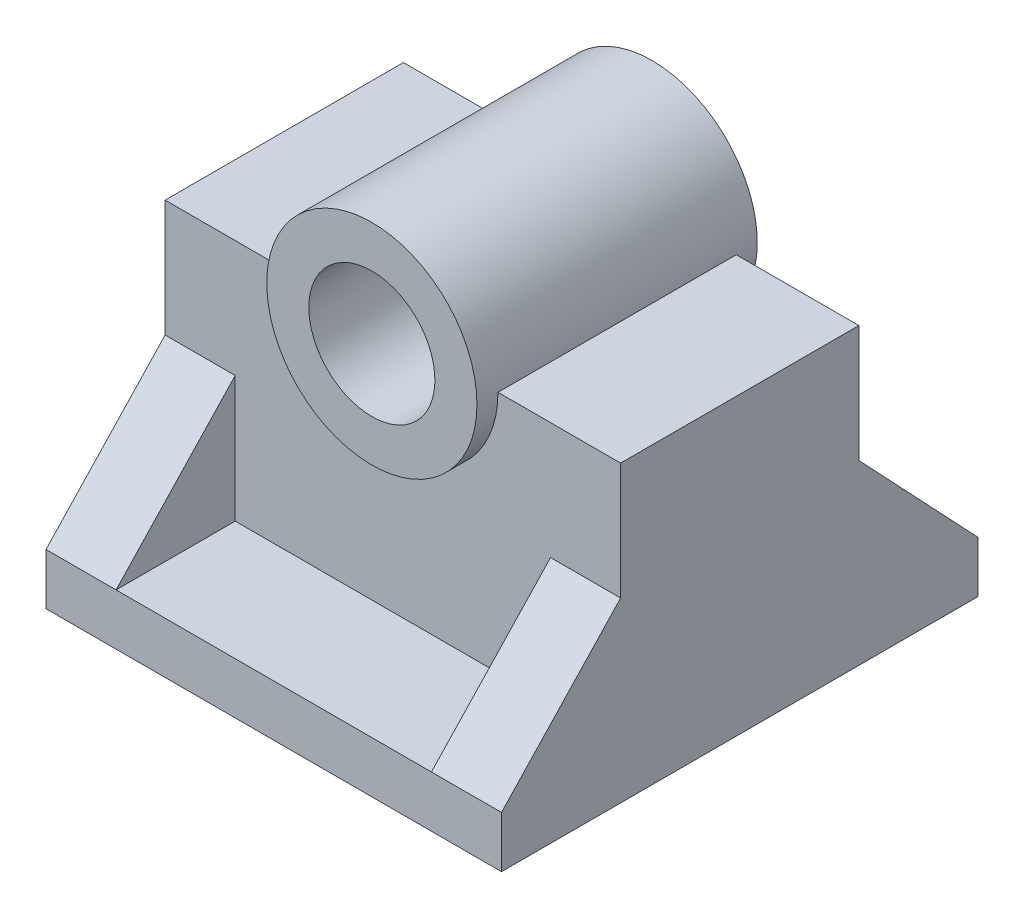
SolidWorks part; units mm, degrees
ref_plane "Front Plane" through (0, 0, 0) normal (0, 0, 1) x (1, 0, 0)
ref_plane "Top Plane" through (0, 0, 0) normal (0, 1, 0) x (1, 0, 0)
ref_plane "Right Plane" through (0, 0, 0) normal (1, 0, 0) x (0, 0, -1)
sketch "Sketch1" plane through (0, 0, 0) normal (1, 0, 0) x (0, 0, -1)
  line L0 (-50.2559, -9.9024) -> (-50.2559, -2.5758)
  line L1 (-50.2559, -2.5758) -> (-33.2559, -2.5758)
  line L2 (-33.2559, -2.5758) -> (-33.2559, 32.0976)
  line L3 (-33.2559, 32.0976) -> (0.7441, 32.0976)
  line L4 (0.7441, 32.0976) -> (0.7441, -2.5758)
  line L5 (0.7441, -2.5758) -> (17.7441, -2.5758)
  line L6 (17.7441, -2.5758) -> (17.7441, -9.9024)
  line L7 (17.7441, -9.9024) -> (-50.2559, -9.9024)
  dimension "D1" = 68
  dimension "D2" = 42
  dimension "D3" = 34
  dimension "D4" = 17
extrude "Boss-Extrude1" add sketch "Sketch1" against normal blind 65
sketch "Sketch2" plane through (0, 0, 0) normal (1, 0, 0) x (0, 0, -1)
  line L0 (-33.2559, 15.4242) -> (-50.2559, -2.5758)
  line L1 (-33.2559, 32.0976) -> (-33.2559, -2.5758) construction
  line L2 (-50.2559, -2.5758) -> (-33.2559, -2.5758)
  line L3 (-33.2559, -2.5758) -> (-33.2559, 15.4242)
  dimension "D1" = 18
extrude "Boss-Extrude2" add sketch "Sketch2" against normal blind 10
sketch "Sketch3" plane through (-65, 0, 0) normal (-1, 0, 0) x (0, 0, 1)
  line L0 (33.2559, 15.4242) -> (50.2559, -2.5758)
  line L1 (50.2559, -2.5758) -> (33.2559, -2.5758)
  line L2 (33.2559, -2.5758) -> (33.2559, 15.4242)
extrude "Boss-Extrude3" add sketch "Sketch3" against normal blind 10
sketch "Sketch4" plane through (-65, 0, 0) normal (-1, 0, 0) x (0, 0, 1)
  line L0 (-17.7441, -2.5758) -> (-0.7441, 15.4242)
  line L1 (-17.7441, -2.5758) -> (-0.7441, -2.5758) construction
  line L2 (-0.7441, -2.5758) -> (-0.7441, 32.0976) construction
  line L3 (-0.7441, 15.4242) -> (-0.7441, -2.5758)
  line L4 (-0.7441, -2.5758) -> (-17.7441, -2.5758)
  dimension "D1" = 18
extrude "Boss-Extrude4" add sketch "Sketch4" against normal blind 10
sketch "Sketch5" plane through (0, 0, 0) normal (1, 0, 0) x (0, 0, -1)
  line L0 (0.7441, 15.4242) -> (17.7441, -2.5758)
  line L1 (17.7441, -2.5758) -> (0.7441, -2.5758)
  line L2 (0.7441, -2.5758) -> (0.7441, 15.4242)
extrude "Boss-Extrude5" add sketch "Sketch5" against normal blind 10
sketch "Sketch6" plane through (0, 0, 33.2559) normal (0, 0, 1) x (1, 0, 0)
  line L0 (-65, 32.0976) -> (0, 32.0976) construction
  circle A0 centre (-32.5, 32.0976) radius 15
extrude "Boss-Extrude6" add sketch "Sketch6" against normal blind 34
sketch "Sketch7" plane through (0, 0, 33.2559) normal (0, 0, 1) x (1, 0, 0)
  circle A0 centre (-32.5, 32.0976) radius 15
extrude "Boss-Extrude7" add sketch "Sketch7" along normal blind 3
sketch "Sketch8" plane through (0, 0, -0.7441) normal (0, 0, -1) x (-1, 0, 0)
  circle A0 centre (32.5, 32.0976) radius 15
extrude "Boss-Extrude8" add sketch "Sketch8" along normal blind 3
sketch "Sketch9" plane through (0, 0, -3.7441) normal (0, 0, -1) x (-1, 0, 0)
  circle A0 centre (32.5, 32.0976) radius 9
extrude "Cut-Extrude1" cut sketch "Sketch9" against normal up to next
